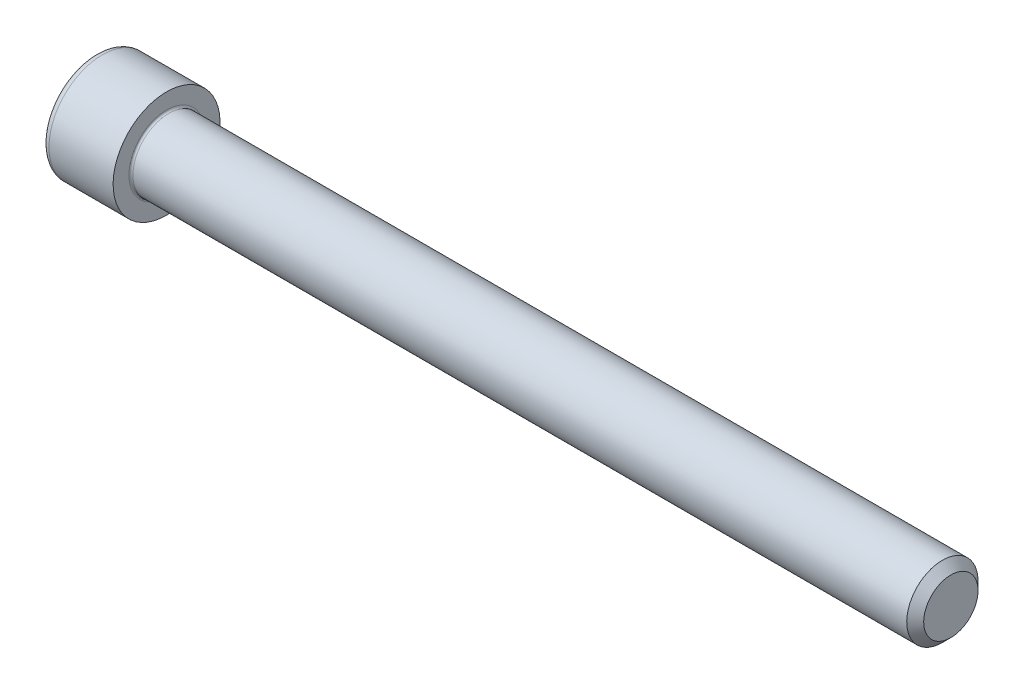
SolidWorks part; units mm, degrees
ref_plane "Front Plane" through (0, 0, 0) normal (0, 0, 1) x (1, 0, 0)
ref_plane "Top Plane" through (0, 0, 0) normal (0, 1, 0) x (1, 0, 0)
ref_plane "Right Plane" through (0, 0, 0) normal (1, 0, 0) x (0, 0, -1)
ref_plane "Plane1"
sketch "Sketch1" plane through (0, 0, 0) normal (0, 0, 1) x (1, 0, 0)
  line L0 (-1.7103, 0) -> (69.85, 0)
  line L1 (69.85, 0) -> (69.85, 3.175)
  line L2 (69.85, 3.175) -> (38.1, 3.175)
  line L3 (38.1, 3.175) -> (34.9249, 3.175)
  line L4 (34.9249, 3.175) -> (0, 3.175)
  line L5 (0, 3.175) -> (0, 4.7625)
  line L6 (0, 4.7625) -> (-6.35, 4.7625)
  line L7 (-6.35, 4.7625) -> (-6.35, 2.757)
  line L8 (-6.35, 2.757) -> (-3.302, 2.757)
  line L9 (-3.302, 2.757) -> (-1.7103, 0)
  line L10 (-1.7103, 0) -> (69.85, 0) construction
  dimension "D1" = 90
  dimension "D2" = 3.1751
  dimension "D3" = 6.35
  dimension "D4" = 3.048
  dimension "D5" = 120
  dimension "D6" = 3.175
  dimension "D7" = 3.175
  dimension "D8" = 2.757
  dimension "D9" = 4.7625
revolve "Body" add sketch "Sketch1" angle 360 about L10
cosmetic thread "Cosmetic Thread1" parameters "D1"=31.75, "D2"=4.8387
ref_plane "Plane2"
sketch "Sketch2" plane through (-6.35, 0, 0) normal (-1, 0, 0) x (0, 0, 1)
  line L0 (2.757, 0) -> (1.3785, -2.3876)
  line L1 (1.3785, -2.3876) -> (-1.3785, -2.3876)
  line L2 (-1.3785, -2.3876) -> (-2.757, 0)
  line L3 (-2.757, 0) -> (-1.3785, 2.3876)
  line L4 (-1.3785, 2.3876) -> (1.3785, 2.3876)
  line L5 (1.3785, 2.3876) -> (2.757, 0)
  circle A0 centre (0, 0) radius 2.757
extrude "Slot" add sketch "Sketch2" against normal up to next contours L0 A0 | L1 A0 | L2 A0 | L3 A0 | L4 A0 | L5 A0
fillet "Thread" radius 0.635 1 edges at (-6.35, -4.7625, 0)
chamfer "Chamfer1" distance 0.7556 distance2 0.7556 1 edges at (69.85, -3.175, 0)
fillet "Fillet2" radius 0.1778 1 edges at (0, -3.175, 0)
